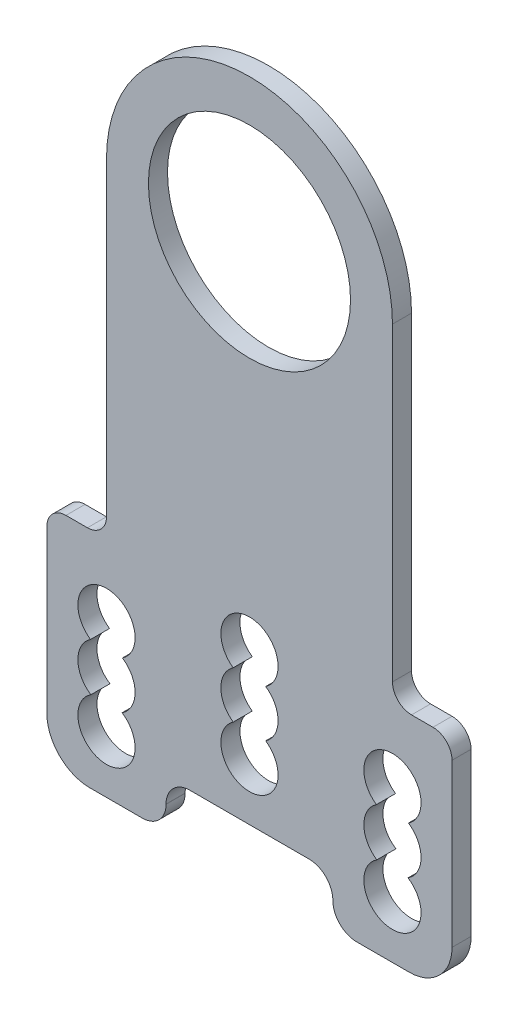
SolidWorks part; units mm, degrees
ref_plane "前视基准面" through (0, 0, 0) normal (0, 0, 1) x (1, 0, 0)
ref_plane "上视基准面" through (0, 0, 0) normal (0, 1, 0) x (1, 0, 0)
ref_plane "右视基准面" through (0, 0, 0) normal (1, 0, 0) x (0, 0, -1)
sketch "草图1" plane through (0, 0, 0) normal (0, 0, 1) x (1, 0, 0)
  line L0 (-15, 0) -> (-15, -32.5)
  line L1 (-17, -34.5) -> (-19.25, -34.5)
  line L2 (15, 0) -> (15, -32.5)
  line L3 (6.25, -52.9741) -> (-6.25, -52.9741)
  line L4 (16.75, -58) -> (11.25, -58)
  line L5 (21.25, -36.5) -> (21.25, -53.5)
  line L6 (17, -34.5) -> (19.25, -34.5)
  line L7 (-21.25, -36.5) -> (-21.25, -53.5)
  line L9 (-16.75, -58) -> (-11.25, -58)
  line L15 (-8.75, -55.4741) -> (-8.75, -55.5)
  line L16 (8.75, -55.4741) -> (8.75, -55.5)
  arc A0 (15, 0) -> (-15, 0) centre (0, 0) ccw
  arc A1 (-17, -34.5) -> (-15, -32.5) centre (-17, -32.5) ccw
  arc A2 (17, -34.5) -> (15, -32.5) centre (17, -32.5) cw
  arc A3 (-16.6386, -49.4871) -> (-13.3614, -49.4871) centre (-15, -52) ccw
  arc A4 (-16.6777, -44.4871) -> (-16.6386, -49.4871) centre (-15, -46.9741) ccw
  arc A5 (-13.3614, -49.4871) -> (-13.3223, -44.4871) centre (-15, -46.9741) ccw
  arc A6 (21.25, -36.5) -> (19.25, -34.5) centre (19.25, -36.5) ccw
  arc A7 (-19.25, -34.5) -> (-21.25, -36.5) centre (-19.25, -36.5) ccw
  circle A8 centre (0, 0) radius 10.6
  arc A9 (-1.7048, -39.5685) -> (-1.7048, -44.5056) centre (0, -42.0371) ccw
  arc A10 (-1.7048, -44.5056) -> (1.7048, -44.5056) centre (0, -46.9741) ccw
  arc A11 (-13.3223, -44.4871) -> (-16.6777, -44.4871) centre (-15, -42) ccw
  arc A14 (1.7048, -39.5685) -> (-1.7048, -39.5685) centre (0, -37.1) ccw
  arc A15 (1.7048, -44.5056) -> (1.7048, -39.5685) centre (0, -42.0371) ccw
  arc A20 (13.3614, -49.4871) -> (16.6386, -49.4871) centre (15, -52) ccw
  arc A21 (16.6386, -49.4871) -> (16.6777, -44.4871) centre (15, -46.9741) ccw
  arc A22 (16.6777, -44.4871) -> (13.3223, -44.4871) centre (15, -42) ccw
  arc A23 (13.3223, -44.4871) -> (13.3614, -49.4871) centre (15, -46.9741) ccw
  arc A29 (-11.25, -58) -> (-8.75, -55.5) centre (-11.25, -55.5) ccw
  arc A30 (-6.25, -52.9741) -> (-8.75, -55.4741) centre (-6.25, -55.4741) ccw
  arc A31 (8.75, -55.4741) -> (6.25, -52.9741) centre (6.25, -55.4741) ccw
  arc A32 (8.75, -55.5) -> (11.25, -58) centre (11.25, -55.5) ccw
  arc A33 (16.75, -58) -> (21.25, -53.5) centre (16.75, -53.5) ccw
  arc A43 (-21.25, -53.5) -> (-16.75, -58) centre (-16.75, -53.5) ccw
  dimension "D1" = 2
  dimension "D2" = 21.2
  dimension "D3" = 15
  dimension "D4" = 58
  dimension "D6" = 4.5
  dimension "D5" = 23.5
  dimension "D7" = 42.5
extrude "凸台-拉伸1" add sketch "草图1" along normal blind 2
